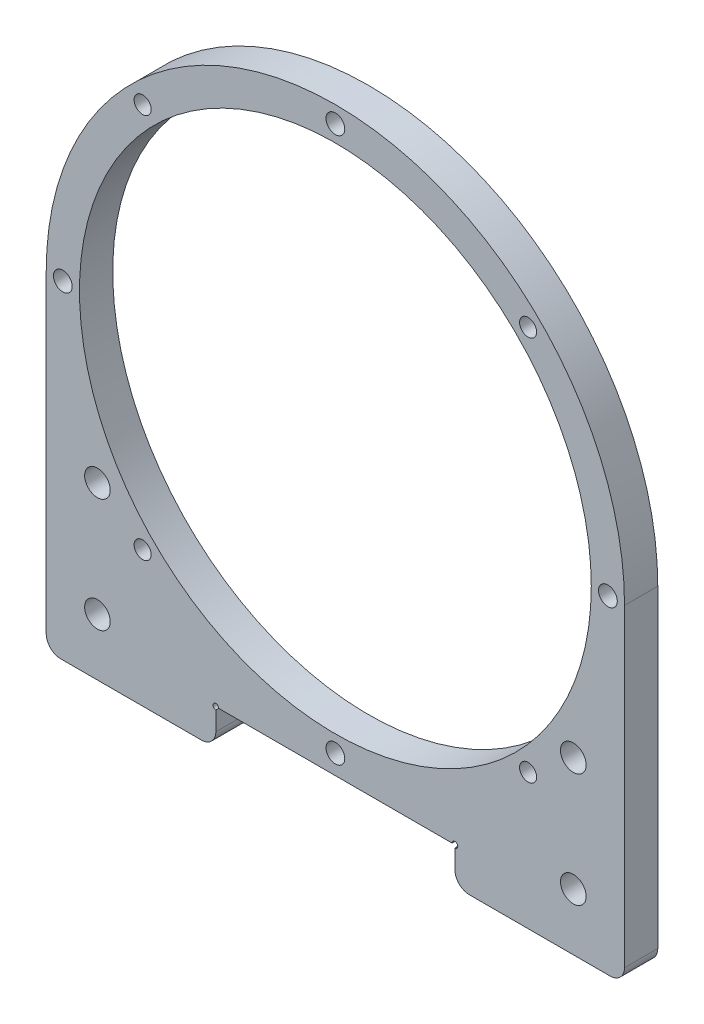
SolidWorks part; units mm, degrees
material "Acrylic (Medium-high impact)"
ref_plane "Front Plane" through (0, 0, 0) normal (0, 0, 1) x (1, 0, 0)
ref_plane "Top Plane" through (0, 0, 0) normal (0, 1, 0) x (1, 0, 0)
ref_plane "Right Plane" through (0, 0, 0) normal (1, 0, 0) x (0, 0, -1)
sketch "Sketch1" plane through (0, 0, 0) normal (0, 0, 1) x (1, 0, 0)
  line L0 (-50.8, 0) -> (-50.8, -57.658)
  line L1 (-50.8, 0) -> (-44.958, 0) construction
  line L2 (0, 0) -> (0, -57.658) construction
  line L4 (50.8, 0) -> (50.8, -57.658)
  line L5 (-33.8556, 33.8556) -> (0, 0) construction
  line L8 (0, 0) -> (0, 47.879) construction
  line L12 (-50.8, -57.658) -> (50.8, -57.658)
  line L13 (-41.8, -47.658) -> (-41.8, -57.658) construction
  line L14 (-41.8, -47.658) -> (-41.8, -27.658) construction
  circle A0 centre (41.8, -47.658) radius 2.25
  circle A1 centre (0, 0) radius 44.958
  arc A2 (-50.8, 0) -> (50.8, 0) centre (0, 0) cw
  circle A3 centre (-47.879, 0) radius 1.65
  circle A4 centre (0, 47.879) radius 1.65
  circle A5 centre (41.8, -27.658) radius 2.25
  circle A6 centre (47.879, 0) radius 1.65
  circle A7 centre (0, -47.879) radius 1.65
  circle A10 centre (-41.8, -27.658) radius 2.25
  circle A11 centre (-33.8556, 33.8556) radius 1.5
  circle A12 centre (33.8556, 33.8556) radius 1.5
  circle A13 centre (33.8556, -33.8556) radius 1.5
  circle A14 centre (-33.8556, -33.8556) radius 1.5
  circle A15 centre (-41.8, -47.658) radius 2.25
  point P29 (0, 0)
  point P46 (0, 0)
  dimension "D2" = 89.916
  dimension "D5" = 3.3
  dimension "D6" = 4
  dimension "D7" = 45
  dimension "D14" = 3
  dimension "D8" = 57.658
  dimension "D17" = 4.5
  dimension "D3" = 101.6
  dimension "D18" = 20
  dimension "D19" = 10
  dimension "D20" = 9
  dimension "D15" = 4
extrude "Boss-Extrude1" add sketch "Sketch1" along normal blind 5.842
sketch "Sketch2" plane through (0, 0, 5.842) normal (0, 0, 1) x (1, 0, 0)
  line L0 (0, -57.658) -> (0, -51.308) construction
  line L1 (-50.8, -57.658) -> (50.8, -57.658) construction
  line L3 (-21, -57.658) -> (21, -57.658)
  line L4 (-21, -57.658) -> (-21, -51.308)
  line L5 (-21, -51.308) -> (21, -51.308)
  line L6 (21, -57.658) -> (21, -51.308)
  dimension "D1" = 6.35
  dimension "D2" = 42
extrude "Cut-Extrude1" cut sketch "Sketch2" against normal through all
sketch "Sketch3" plane through (0, 0, 5.842) normal (0, 0, 1) x (1, 0, 0)
  circle A0 centre (-21, -51.308) radius 0.5
  circle A1 centre (21, -51.308) radius 0.5
  dimension "D1" = 1
extrude "Cut-Extrude2" cut sketch "Sketch3" against normal through all
fillet "Fillet1" radius 2.54 4 edges at (50.8, -57.658, 2.921) (21, -57.658, 2.921) (-21, -57.658, 2.921) (-50.8, -57.658, 2.921)
